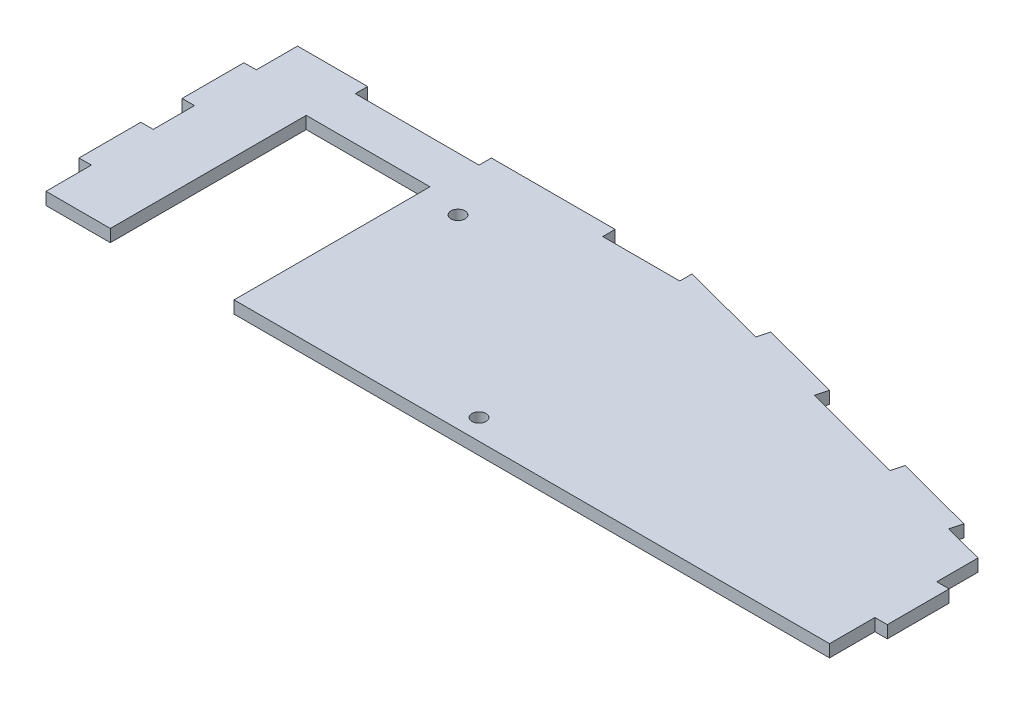
SolidWorks part; units mm, degrees
ref_plane "Front Plane" through (0, 0, 0) normal (0, 0, 1) x (1, 0, 0)
ref_plane "Top Plane" through (0, 0, 0) normal (0, 1, 0) x (1, 0, 0)
ref_plane "Right Plane" through (0, 0, 0) normal (1, 0, 0) x (0, 0, -1)
other "Configuration Table"
sketch "Sketch1" plane through (0, 0, 0) normal (0, 1, 0) x (1, 0, 0)
  line L1 (98, -30.5) -> (-98, -30.5)
  line L2 (98, -30.5) -> (98, 30.5)
  line L3 (98, 30.5) -> (-98, 30.5)
  line L4 (-98, -30.5) -> (-98, 30.5)
  line L5 (98, -30.5) -> (-98, 30.5) construction
  line L6 (98, 30.5) -> (-98, -30.5) construction
  point P0 (0, 0)
  dimension "D1" = 61
  dimension "D2" = 196
extrude "Boss-Extrude1" add sketch "Sketch1" along normal blind 3
sketch "Sketch2" plane through (0, 3, 0) normal (0, 1, 0) x (1, 0, 0)
  line L0 (-79.4, -30.5) -> (-79.4, 17)
  line L1 (-98, -30.5) -> (98, -30.5) construction
  line L2 (-79.4, 17) -> (-49.4, 17)
  line L3 (-49.4, 17) -> (-49.4, -30.5)
  line L4 (-49.4, -30.5) -> (-79.4, -30.5)
  line L5 (-95, 30.5) -> (-98, 30.5)
  line L6 (98, 30.5) -> (-98, 30.5) construction
  line L7 (-98, 30.5) -> (-98, 20.5)
  line L8 (-98, 30.5) -> (-98, -30.5) construction
  line L9 (-98, 20.5) -> (-95, 20.5)
  line L10 (-95, 20.5) -> (-95, 30.5)
  line L11 (-98, 5.5) -> (-95, 5.5)
  line L12 (-95, 5.5) -> (-95, -4.5)
  line L13 (-95, -4.5) -> (-98, -4.5)
  line L14 (-98, -4.5) -> (-98, 5.5)
  line L15 (-98, -19.5) -> (-95, -19.5)
  line L16 (-95, -19.5) -> (-95, -30.5)
  line L17 (-95, -30.5) -> (-98, -30.5)
  line L18 (-98, -30.5) -> (-98, -19.5)
  line L19 (98, 5.5) -> (98, -4.5)
  line L20 (98, -30.5) -> (98, 30.5) construction
  line L21 (98, -4.5) -> (95, -4.5)
  line L22 (95, -4.5) -> (95, 5.5)
  line L23 (95, 5.5) -> (98, 5.5)
  line L24 (98, -30.5) -> (98, -19.5)
  line L25 (98, -19.5) -> (95, -19.5)
  line L26 (95, -19.5) -> (95, -30.5)
  line L27 (95, -30.5) -> (98, -30.5)
  line L28 (-18, 30.5) -> (-18, 27.5)
  line L40 (-78, 30.5) -> (-78, 27.5)
  line L41 (-78, 27.5) -> (-48, 27.5)
  line L42 (-48, 27.5) -> (-48, 30.5)
  line L43 (-78, 30.5) -> (-48, 30.5)
  line L44 (-18, 27.5) -> (12, 27.5)
  line L45 (12, 27.5) -> (12, 30.5)
  line L46 (-18, 30.5) -> (12, 30.5)
  line L47 (42, 30.5) -> (42, 27.5)
  line L48 (42, 27.5) -> (72, 27.5)
  line L49 (72, 27.5) -> (72, 30.5)
  line L50 (42, 30.5) -> (72, 30.5)
  line L51 (98, 20.5) -> (95, 20.5)
  line L52 (95, 20.5) -> (95, 30.5)
  line L53 (95, 30.5) -> (98, 30.5)
  line L54 (98, 30.5) -> (98, 20.5)
  circle A0 centre (-40.09, 14.5) radius 1.7
  circle A1 centre (5, -25.5) radius 1.7
  dimension "D4" = 45
  dimension "D6" = 103
  dimension "D1" = 18.6
  dimension "D2" = 47.5
  dimension "D3" = 30
  dimension "D5" = 57.91
  dimension "D7" = 3
  dimension "D8" = 10
  dimension "D9" = 11
  dimension "D10" = 10
  dimension "D11" = 15
  dimension "D12" = 3
  dimension "D13" = 30
  dimension "D14" = 30
  dimension "D15" = 30
  dimension "D16" = 30
  dimension "D17" = 30
  dimension "D20" = 20
  dimension "D22" = 3
extrude "Cut-Extrude1" cut sketch "Sketch2" against normal blind 3
sketch "Sketch3" plane through (0, 3, 0) normal (0, 1, 0) x (1, 0, 0)
  line L0 (12, 30.5) -> (98, 30.5)
  line L1 (98, 30.5) -> (98, 5.5)
  line L2 (98, 5.5) -> (95, 5.5)
  line L3 (12, 30.5) -> (12, 27.5)
  line L4 (12, 27.5) -> (95, 5.5) construction
  line L5 (95, 5.5) -> (85.3338, 8.0621)
  line L6 (85.3338, 8.0621) -> (86.1024, 10.962)
  line L7 (86.1024, 10.962) -> (66.77, 16.0862)
  line L8 (66.77, 16.0862) -> (66.0014, 13.1864)
  line L9 (66.0014, 13.1864) -> (40.9986, 19.8136)
  line L10 (40.9986, 19.8136) -> (41.7673, 22.7135)
  line L11 (41.7673, 22.7135) -> (22.4348, 27.8377)
  line L12 (22.4348, 27.8377) -> (21.6662, 24.9379)
  line L13 (21.6662, 24.9379) -> (12, 27.5)
  dimension "D1" = 10
  dimension "D2" = 20
  dimension "D3" = 10
  dimension "D4" = 20
  dimension "D5" = 3
extrude "Cut-Extrude2" cut sketch "Sketch3" against normal blind 10
sketch "Sketch5" plane through (0, 3, 0) normal (0, 1, 0) x (1, 0, 0)
  line L0 (12, 27.5) -> (0.6818, 30.5)
  line L1 (12, 27.5) -> (21.6662, 24.9379) construction
  line L2 (0.6818, 30.5) -> (0.6818, 27.5)
  line L3 (-18, 27.5) -> (12, 27.5) construction
  line L4 (0.6818, 27.5) -> (12, 27.5)
extrude "Boss-Extrude2" add sketch "Sketch5" against normal blind 3
